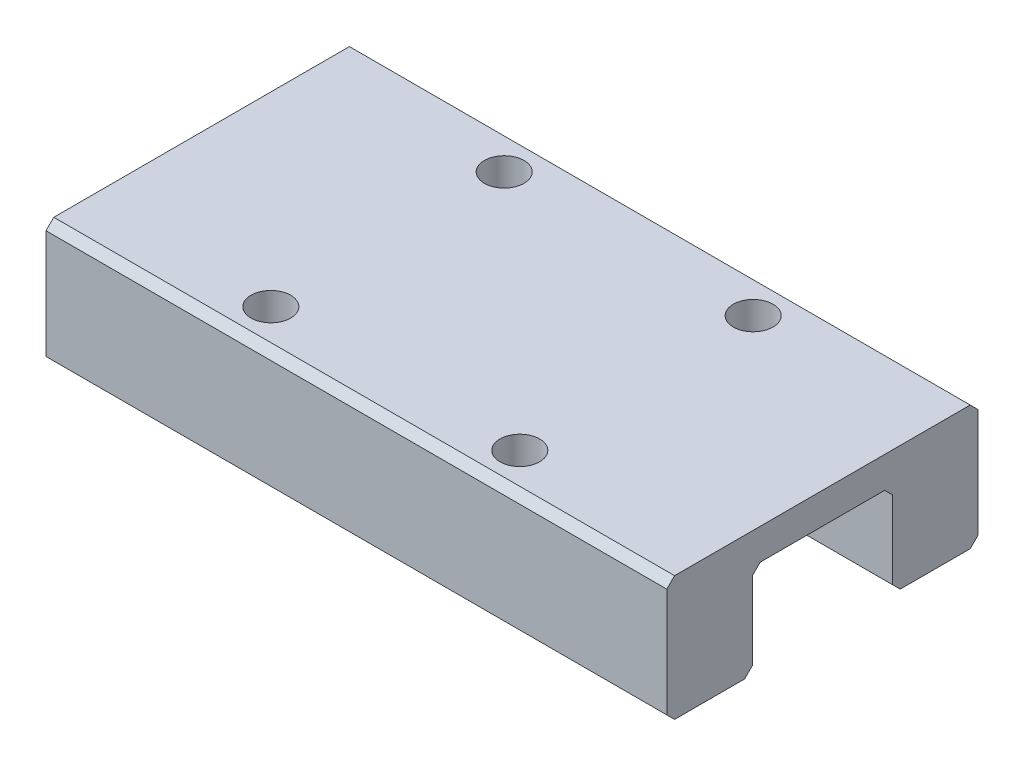
SolidWorks part; units mm, degrees
material "普通碳钢"
ref_plane "前视基准面" through (0, 0, 0) normal (0, 0, 1) x (1, 0, 0)
ref_plane "上视基准面" through (0, 0, 0) normal (0, 1, 0) x (1, 0, 0)
ref_plane "右视基准面" through (0, 0, 0) normal (1, 0, 0) x (0, 0, -1)
sketch "草图2" plane through (0, 0, 0) normal (1, 0, 0) x (0, 0, -1)
  line L0 (-4.5, 0) -> (4.5, 0)
  line L1 (4.5, 0) -> (4.5, -6)
  line L2 (4.5, -6) -> (10, -6)
  line L3 (10, -6) -> (10, 2)
  line L4 (0, 55.2379) -> (0, -46.8755) construction
  line L5 (10, 2) -> (-10, 2)
  line L6 (-10, -6) -> (-10, 2)
  line L7 (-4.5, -6) -> (-10, -6)
  line L8 (-4.5, 0) -> (-4.5, -6)
  point P10 (0, 2)
  point P11 (0, 0)
  dimension "D1" = 8
  dimension "D2" = 2
  dimension "D3" = 4.5
  dimension "D4" = 10
extrude "拉伸1" add sketch "草图2" along normal blind 39.9
chamfer "倒角1" distance 0.5 angle 45 8 edges at (19.95, 0, 4.5) (19.95, -6, -4.5) (19.95, 0, -4.5) (19.95, -6, 10) (19.95, -6, 4.5) (19.95, -6, -10) (19.95, 2, -10) (19.95, 2, 10)
sketch "草图3" plane through (0, 2, 0) normal (0, 1, 0) x (1, 0, 0)
  line L0 (19.95, 23.1296) -> (19.95, -26.0824) construction
  line L1 (39.9, 9.5) -> (39.9, -9.5) construction
  line L2 (-5.6521, 0) -> (44.7927, 0) construction
  circle A0 centre (11.95, 7.5) radius 1.275
  circle A1 centre (27.95, 7.5) radius 1.275
  circle A2 centre (27.95, -7.5) radius 1.275
  circle A3 centre (11.95, -7.5) radius 1.275
  dimension "D2" = 8
  dimension "D3" = 7.5
  dimension "D4" = 2.55
  dimension "D1" = 19.95
extrude "拉伸2" cut sketch "草图3" against normal blind 3
cosmetic thread "装饰螺纹线9" parameters "D2"=3
cosmetic thread "装饰螺纹线10" parameters "D2"=3
cosmetic thread "装饰螺纹线11" parameters "D2"=3
cosmetic thread "装饰螺纹线12" parameters "D2"=3
